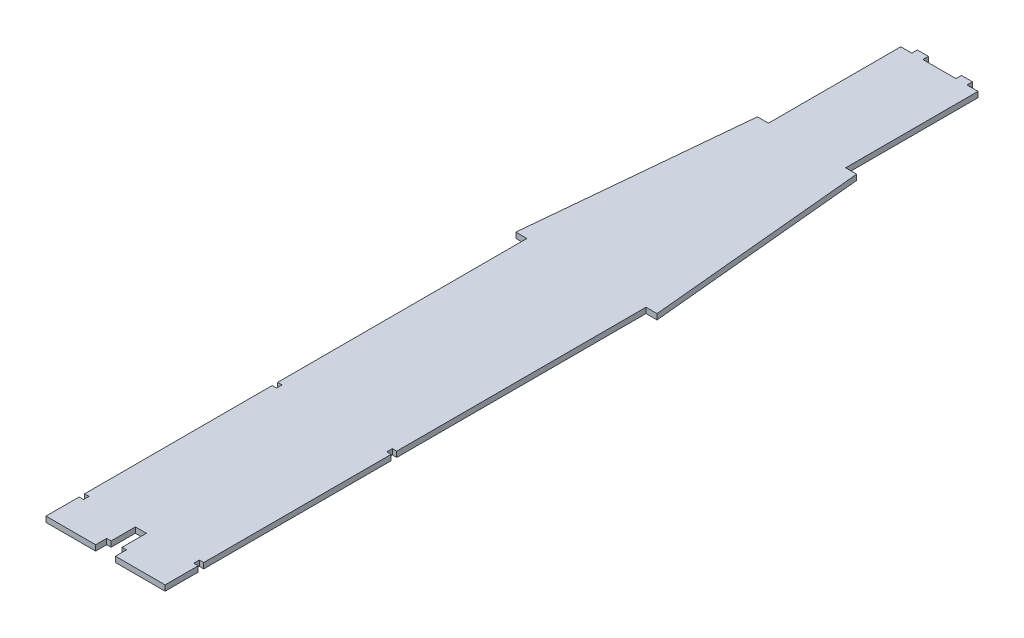
SolidWorks part; units mm, degrees
material "Cedar"
ref_plane "Front Plane" through (0, 0, 0) normal (0, 0, 1) x (1, 0, 0)
ref_plane "Top Plane" through (0, 0, 0) normal (0, 1, 0) x (1, 0, 0)
ref_plane "Right Plane" through (0, 0, 0) normal (1, 0, 0) x (0, 0, -1)
sketch "Sketch1" plane through (0, 0, 0) normal (0, 1, 0) x (1, 0, 0)
  line L0 (0, 276.86) -> (-6.35, 276.86)
  line L1 (0, 0) -> (68.58, 0)
  line L2 (0, 0) -> (0, 276.86)
  line L3 (0, 276.86) -> (68.58, 276.86)
  line L4 (68.58, 0) -> (68.58, 276.86)
  line L5 (68.58, 276.86) -> (74.93, 276.86)
  line L6 (-6.35, 276.86) -> (5.715, 403.86)
  line L7 (5.715, 403.86) -> (62.865, 403.86)
  line L8 (62.865, 403.86) -> (74.93, 276.86)
  line L9 (34.29, 403.86) -> (34.29, 0) construction
  line L10 (-87.9324, 230.1004) -> (150.5604, 230.1004) construction
  line L11 (12.065, 403.86) -> (56.515, 403.86)
  line L12 (12.065, 403.86) -> (12.065, 480.06)
  line L13 (12.065, 480.06) -> (56.515, 480.06)
  line L14 (56.515, 403.86) -> (56.515, 480.06)
  line L15 (18.415, 480.06) -> (24.765, 480.06)
  line L16 (18.415, 480.06) -> (18.415, 483.235)
  line L17 (18.415, 483.235) -> (24.765, 483.235)
  line L18 (24.765, 480.06) -> (24.765, 483.235)
  line L19 (43.815, 480.06) -> (50.165, 480.06)
  line L20 (43.815, 480.06) -> (43.815, 483.235)
  line L21 (43.815, 483.235) -> (50.165, 483.235)
  line L22 (50.165, 480.06) -> (50.165, 483.235)
  point P4 (85.09, 127)
  dimension "D3" = 6.35
  dimension "D4" = 6.35
  dimension "D5" = 127
  dimension "D6" = 57.15
  dimension "D7" = 44.45
  dimension "D8" = 76.2
  dimension "D9" = 6.35
  dimension "D10" = 3.175
  dimension "D11" = 9.525
  dimension "D12" = 127
  dimension "D13" = 50.8
extrude "Boss-Extrude1" add sketch "Sketch1" along normal blind 3.175 contours L9 L3 L2 L1 | L3 L9 L1 L4 | L7 L9 L3 L5 L8 | L9 L7 L6 L0 L3 | L7 L11 L14 L13 L12 | L13 L18 L17 L16 | L13 L22 L21 L20
sketch "Sketch2" plane through (0, 0, 0) normal (0, 0, 1) x (1, 0, 0)
  line L0 (34.29, 0) -> (34.29, 3.175) construction
  line L1 (0, 0) -> (68.58, 0) construction
  line L2 (0, 3.175) -> (68.58, 3.175) construction
sketch "Sketch3" plane through (0, 3.175, 0) normal (0, 1, 0) x (1, 0, 0)
  line L0 (0, 0) -> (0, 276.86) construction
  line L1 (0, 22.225) -> (2.54, 22.225)
  line L2 (0, 22.225) -> (0, 19.05)
  line L3 (0, 19.05) -> (2.54, 19.05)
  line L4 (2.54, 22.225) -> (2.54, 19.05)
  line L5 (68.58, 0) -> (68.58, 276.86) construction
  line L6 (68.58, 22.225) -> (66.04, 22.225)
  line L7 (68.58, 22.225) -> (68.58, 19.05)
  line L8 (68.58, 19.05) -> (66.04, 19.05)
  line L9 (66.04, 22.225) -> (66.04, 19.05)
  line L10 (0, 0) -> (68.58, 0) construction
  line L12 (0, 133.35) -> (2.54, 133.35)
  line L13 (0, 133.35) -> (0, 130.175)
  line L14 (0, 130.175) -> (2.54, 130.175)
  line L15 (2.54, 133.35) -> (2.54, 130.175)
  line L16 (68.58, 133.35) -> (66.04, 133.35)
  line L17 (68.58, 133.35) -> (68.58, 130.175)
  line L18 (68.58, 130.175) -> (66.04, 130.175)
  line L19 (66.04, 133.35) -> (66.04, 130.175)
  dimension "D1" = 19.05
  dimension "D2" = 3.175
  dimension "D3" = 63.5
  dimension "D4" = 107.95
extrude "Cut-Extrude1" cut sketch "Sketch3" against normal through all
sketch "Sketch4" plane through (0, 3.175, 0) normal (0, 1, 0) x (1, 0, 0)
  line L0 (0, 0) -> (68.58, 0) construction
  line L1 (31.115, 0) -> (37.465, 0)
  line L2 (31.115, 0) -> (31.115, 20.32)
  line L3 (31.115, 20.32) -> (37.465, 20.32)
  line L4 (37.465, 0) -> (37.465, 20.32)
  line L5 (34.29, 0) -> (34.29, 20.32) construction
  line L7 (28.575, 6.35) -> (40.005, 6.35)
  line L8 (28.575, 6.35) -> (28.575, 0)
  line L9 (28.575, 0) -> (40.005, 0)
  line L10 (40.005, 6.35) -> (40.005, 0)
  line M31 (0, 0) -> (68.58, 0)
  dimension "D1" = 6.35
  dimension "D2" = 20.32
  dimension "D3" = 11.43
  dimension "D4" = 6.35
extrude "Cut-Extrude2" cut sketch "Sketch4" against normal through all contours L7 L8 L2 M31 | L5 L7 L2 M31 | L5 L9 L4 L7 | L10 L7 L4 M31 | L5 L7 L4 L3 | L7 L5 L3 L2
